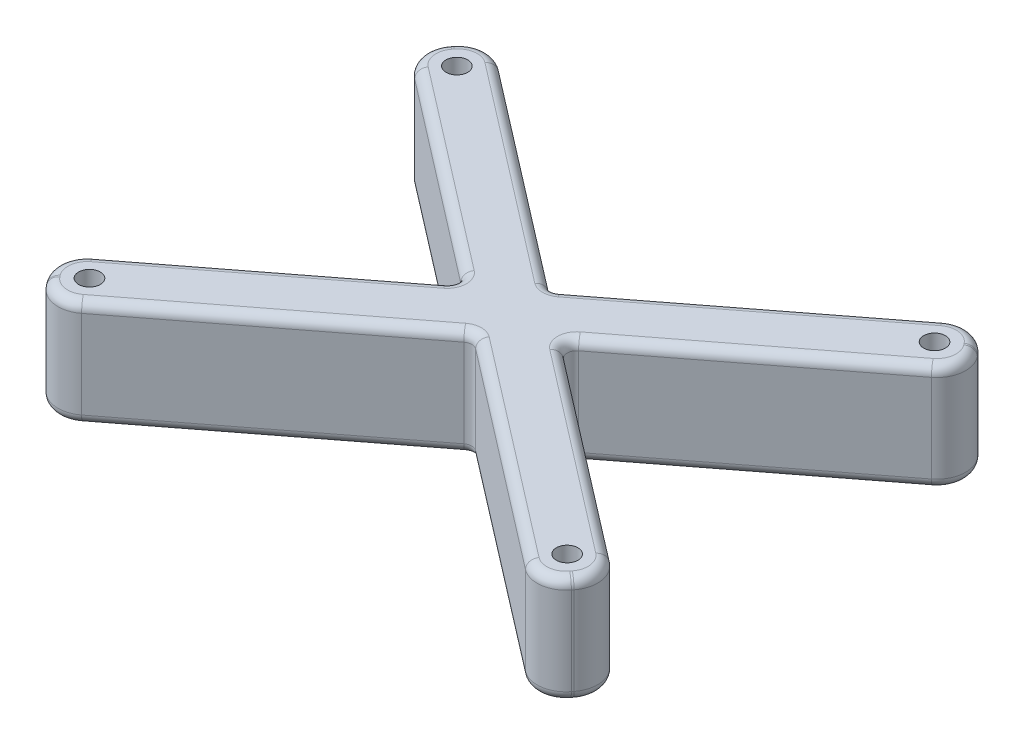
SolidWorks part; units mm, degrees
ref_plane "Front Plane" through (0, 0, 0) normal (0, 0, 1) x (1, 0, 0)
ref_plane "Top Plane" through (0, 0, 0) normal (0, 1, 0) x (1, 0, 0)
ref_plane "Right Plane" through (0, 0, 0) normal (1, 0, 0) x (0, 0, -1)
sketch "Sketch1" plane through (0, 0, 0) normal (0, 1, 0) x (1, 0, 0)
  line L0 (-49.53, 38.1) -> (49.53, -38.1) construction
  line L1 (-49.53, -38.1) -> (49.53, 38.1) construction
  line L2 (-50.7844, 46.884) -> (-58.3419, 37.0593)
  line L3 (-58.3419, 37.0593) -> (-10.1648, 0)
  line L4 (-10.1648, 0) -> (-58.3419, -37.0593)
  line L5 (-58.3419, -37.0593) -> (-50.7844, -46.884)
  line L6 (-50.7844, -46.884) -> (0, -7.8191)
  line L7 (0, -7.8191) -> (50.7844, -46.884)
  line L8 (50.7844, -46.884) -> (58.3419, -37.0593)
  line L9 (58.3419, -37.0593) -> (10.1648, 0)
  line L10 (10.1648, 0) -> (58.3419, 37.0593)
  line L11 (58.3419, 37.0593) -> (50.7844, 46.884)
  line L12 (50.7844, 46.884) -> (0, 7.8191)
  line L13 (0, 7.8191) -> (-50.7844, 46.884)
  circle A0 centre (-49.53, 38.1) radius 2.25
  circle A1 centre (-49.53, -38.1) radius 2.25
  circle A2 centre (49.53, -38.1) radius 2.25
  circle A3 centre (49.53, 38.1) radius 2.25
  point P4 (0, 0)
  dimension "D11" = 4.5
  dimension "D1" = 99.06
  dimension "D2" = 76.2
  dimension "D3" = 12.3952
  dimension "D4" = 12.3952
  dimension "D5" = 12.3952
  dimension "D6" = 12.3952
  dimension "D7" = 6.35
  dimension "D8" = 6.35
  dimension "D9" = 6.35
  dimension "D10" = 6.35
extrude "Boss-Extrude1" add sketch "Sketch1" along normal blind 22.2504
fillet "Fillet1" radius 6 8 edges at (50.7844, 11.1252, -46.884) (58.3419, 11.1252, -37.0593) (58.3419, 11.1252, 37.0593) (50.7844, 11.1252, 46.884) (-50.7844, 11.1252, 46.884) (-58.3419, 11.1252, 37.0593) (-50.7844, 11.1252, -46.884) (-58.3419, 11.1252, -37.0593)
fillet "Fillet2" radius 2 4 edges at (10.1648, 11.1252, 0) (0, 11.1252, -7.8191) (-10.1648, 11.1252, 0) (0, 11.1252, 7.8191)
fillet "Fillet4" radius 2 48 edges at (-23.624, 0, 25.9914) (0, 0, 8.3424) (23.624, 0, 25.9914) (50.463, 0, 44.4196) (54.5632, 0, 41.9717) (55.8775, 0, 37.3807) (32.9059, 0, 17.4931) (11.4451, 0, 0) (32.9059, 0, -17.4931) (55.8775, 0, -37.3807) (54.5632, 0, -41.9717) (50.463, 0, -44.4196) (23.624, 0, -25.9914) (0, 0, -8.3424) (-23.624, 0, -25.9914) (-50.463, 0, -44.4196) (-54.5632, 0, -41.9717) (-55.8775, 0, -37.3807) (-32.9059, 0, -17.4931) (-11.4451, 0, 0) (-32.9059, 0, 17.4931) (-55.8775, 0, 37.3807) (-54.5632, 0, 41.9717) (-55.8775, 22.2504, -37.3807) (-54.5632, 22.2504, -41.9717) (-50.463, 22.2504, -44.4196) (-23.624, 22.2504, -25.9914) (0, 22.2504, -8.3424) (23.624, 22.2504, -25.9914) (50.463, 22.2504, -44.4196) (54.5632, 22.2504, -41.9717) (55.8775, 22.2504, -37.3807) (32.9059, 22.2504, -17.4931) (11.4451, 22.2504, 0) (32.9059, 22.2504, 17.4931) (55.8775, 22.2504, 37.3807) (54.5632, 22.2504, 41.9717) (50.463, 22.2504, 44.4196) (23.624, 22.2504, 25.9914) (0, 22.2504, 8.3424) (-23.624, 22.2504, 25.9914) (-50.463, 22.2504, 44.4196) (-54.5632, 22.2504, 41.9717) (-55.8775, 22.2504, 37.3807) (-32.9059, 22.2504, 17.4931) (-11.4451, 22.2504, 0) (-50.463, 0, 44.4196) (-32.9059, 22.2504, -17.4931)
